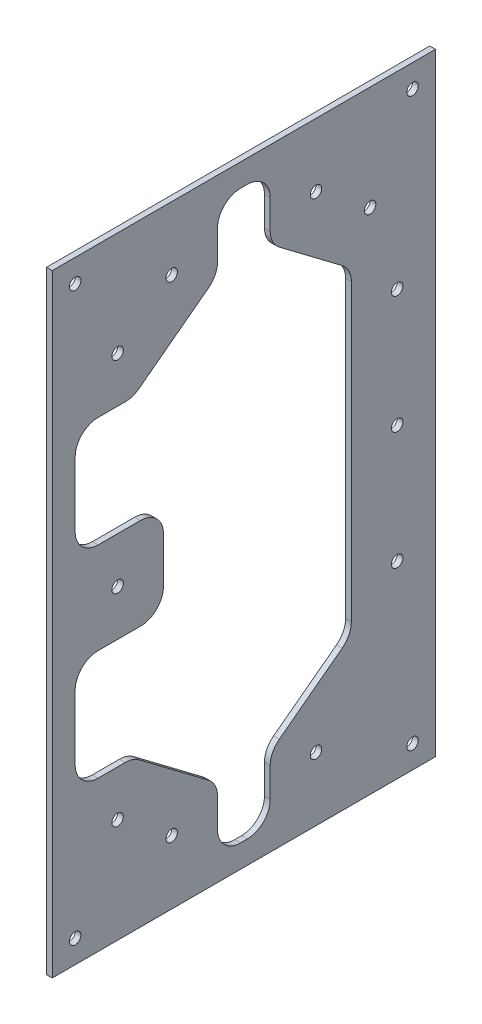
SolidWorks part; units mm, degrees
material "6061-T6 (SS)"
ref_plane "Front Plane" through (0, 0, 0) normal (0, 0, 1) x (1, 0, 0)
ref_plane "Top Plane" through (0, 0, 0) normal (0, 1, 0) x (1, 0, 0)
ref_plane "Right Plane" through (0, 0, 0) normal (1, 0, 0) x (0, 0, -1)
sketch "Sketch1" plane through (0, 0, 0) normal (1, 0, 0) x (0, 0, -1)
  line L0 (0, -169.8625) -> (212.5, -169.8625) construction
  line L1 (0, 0) -> (212.5, 0)
  line L2 (0, 0) -> (0, -339.725)
  line L3 (0, -339.725) -> (212.5, -339.725)
  line L4 (212.5, 0) -> (212.5, -339.725)
  line L5 (153.5, -35.2425) -> (59, -35.2425) construction
  line L6 (191.25, -104.5325) -> (191.25, -169.8625) construction
  line L7 (13.5, -50.2425) -> (59, -50.2425) construction
  line L8 (36.25, -50.2425) -> (36.25, -169.8625) construction
  line L9 (106.25, 0) -> (106.25, -339.725) construction
  line L10 (173.5, -104.5325) -> (191.25, -104.5325) construction
  circle A0 centre (12.7, -12.7) radius 3.175
  circle A1 centre (199.8, -12.7) radius 3.175
  circle A2 centre (66.25, -35.2425) radius 3.175
  circle A3 centre (146.25, -35.2425) radius 3.175
  circle A4 centre (176.25, -57.8625) radius 3.175
  circle A5 centre (36.25, -57.8625) radius 3.175
  circle A6 centre (191.25, -104.5325) radius 3.175
  circle A7 centre (36.25, -169.8625) radius 3.175
  circle A8 centre (191.25, -169.8625) radius 3.175
  circle A9 centre (36.25, -281.8625) radius 3.175
  circle A10 centre (66.25, -304.4825) radius 3.175
  circle A11 centre (12.7, -327.025) radius 3.175
  circle A12 centre (199.8, -327.025) radius 3.175
  circle A13 centre (146.25, -304.4825) radius 3.175
  circle A14 centre (191.25, -235.1925) radius 3.175
  dimension "D1" = 339.725
  dimension "D2" = 212.5
  dimension "D3" = 40
  dimension "D4" = 112
  dimension "D5" = 85
  dimension "D6" = 157.1625
extrude "Boss-Extrude1" add sketch "Sketch1" along normal blind 3.175
sketch "Sketch2" plane through (3.175, 0, 0) normal (1, 0, 0) x (0, 0, -1)
  line L1 (165.85, -88.1617) -> (165.85, -251.5633)
  line L4 (0, 0) -> (0, -339.725)
  line L5 (0, -339.725) -> (212.5, -339.725)
  line L6 (212.5, -339.725) -> (212.5, 0)
  line L7 (212.5, 0) -> (0, 0)
  line L8 (0, 0) -> (0, -339.725)
  line L9 (0, -339.725) -> (212.5, -339.725)
  line L10 (212.5, -339.725) -> (212.5, 0)
  line L11 (212.5, 0) -> (0, 0)
  line L14 (25.4, -144.4625) -> (48.95, -144.4625)
  line L15 (25.4, -83.2625) -> (40.5014, -83.2625)
  line L16 (12.7, -95.9625) -> (12.7, -131.7625)
  line L17 (34.7163, -60.6425) -> (37.7837, -60.6425)
  line L18 (61.65, -70.5625) -> (61.65, -70.522)
  line L19 (61.65, -182.5625) -> (61.65, -157.1625)
  line L20 (36.25, -57.8625) -> (66.25, -35.2425) construction
  line L21 (48.1473, -80.703) -> (86.5959, -51.7127)
  line L22 (91.65, -25.4) -> (91.65, -41.5722)
  line L23 (120.85, -25.4) -> (120.85, -41.5722)
  line L24 (104.35, -12.7) -> (108.15, -12.7)
  line L25 (176.25, -57.8625) -> (146.25, -35.2425) construction
  line L26 (125.9041, -51.7127) -> (160.7959, -78.0212)
  line L27 (0, -169.8625) -> (212.5, -169.8625) construction
  line L28 (176.25, -281.8625) -> (146.25, -304.4825) construction
  line L29 (36.25, -281.8625) -> (66.25, -304.4825) construction
  line L30 (125.9041, -288.0123) -> (160.7959, -261.7038)
  line L31 (104.35, -327.025) -> (108.15, -327.025)
  line L32 (120.85, -314.325) -> (120.85, -298.1528)
  line L33 (91.65, -314.325) -> (91.65, -298.1528)
  line L34 (48.1473, -259.022) -> (86.5959, -288.0123)
  line L35 (61.65, -269.1625) -> (61.65, -269.203)
  line L36 (34.7163, -279.0825) -> (37.7837, -279.0825)
  line L37 (12.7, -243.7625) -> (12.7, -207.9625)
  line L38 (25.4, -256.4625) -> (40.5014, -256.4625)
  line L39 (25.4, -195.2625) -> (48.95, -195.2625)
  circle A0 centre (176.25, -57.8625) radius 3.175 construction
  circle A1 centre (146.25, -35.2425) radius 3.175 construction
  circle A2 centre (66.25, -35.2425) radius 3.175 construction
  circle A3 centre (36.25, -57.8625) radius 3.175 construction
  circle A4 centre (36.25, -169.8625) radius 3.175 construction
  circle A5 centre (36.25, -281.8625) radius 3.175 construction
  circle A6 centre (66.25, -304.4825) radius 3.175 construction
  circle A7 centre (146.25, -304.4825) radius 3.175 construction
  circle A8 centre (191.25, -235.1925) radius 3.175 construction
  circle A9 centre (191.25, -169.8625) radius 3.175 construction
  circle A10 centre (191.25, -104.5325) radius 3.175 construction
  circle A11 centre (176.25, -57.8625) radius 3.175 construction
  circle A12 centre (146.25, -35.2425) radius 3.175 construction
  circle A13 centre (66.25, -35.2425) radius 3.175 construction
  circle A14 centre (36.25, -57.8625) radius 3.175 construction
  circle A15 centre (36.25, -169.8625) radius 3.175 construction
  circle A16 centre (36.25, -281.8625) radius 3.175 construction
  circle A17 centre (66.25, -304.4825) radius 3.175 construction
  circle A18 centre (146.25, -304.4825) radius 3.175 construction
  circle A19 centre (191.25, -235.1925) radius 3.175 construction
  circle A20 centre (191.25, -169.8625) radius 3.175 construction
  circle A21 centre (191.25, -104.5325) radius 3.175 construction
  arc A28 (48.95, -144.4625) -> (61.65, -157.1625) centre (48.95, -157.1625) cw
  arc A29 (12.7, -131.7625) -> (25.4, -144.4625) centre (25.4, -131.7625) ccw
  arc A30 (12.7, -95.9625) -> (25.4, -83.2625) centre (25.4, -95.9625) cw
  arc A33 (165.85, -88.1617) -> (160.7959, -78.0212) centre (153.15, -88.1617) ccw
  arc A34 (125.9041, -51.7127) -> (120.85, -41.5722) centre (133.55, -41.5722) cw
  arc A35 (108.15, -12.7) -> (120.85, -25.4) centre (108.15, -25.4) cw
  arc A36 (104.35, -12.7) -> (91.65, -25.4) centre (104.35, -25.4) ccw
  arc A37 (86.5959, -51.7127) -> (91.65, -41.5722) centre (78.95, -41.5722) ccw
  arc A38 (48.1473, -80.703) -> (40.5014, -83.2625) centre (40.5014, -70.5625) cw
  circle A39 centre (36.25, -281.8625) radius 3.175 construction
  circle A40 centre (66.25, -304.4825) radius 3.175 construction
  circle A41 centre (146.25, -304.4825) radius 3.175 construction
  circle A42 centre (176.25, -281.8625) radius 3.175 construction
  arc A43 (48.1473, -259.022) -> (40.5014, -256.4625) centre (40.5014, -269.1625) ccw
  arc A44 (86.5959, -288.0123) -> (91.65, -298.1528) centre (78.95, -298.1528) cw
  arc A45 (104.35, -327.025) -> (91.65, -314.325) centre (104.35, -314.325) cw
  arc A46 (108.15, -327.025) -> (120.85, -314.325) centre (108.15, -314.325) ccw
  arc A47 (125.9041, -288.0123) -> (120.85, -298.1528) centre (133.55, -298.1528) ccw
  arc A48 (165.85, -251.5633) -> (160.7959, -261.7038) centre (153.15, -251.5633) cw
  arc A49 (12.7, -243.7625) -> (25.4, -256.4625) centre (25.4, -243.7625) ccw
  arc A50 (12.7, -207.9625) -> (25.4, -195.2625) centre (25.4, -207.9625) cw
  arc A51 (48.95, -195.2625) -> (61.65, -182.5625) centre (48.95, -182.5625) ccw
  point P73 (61.65, -83.2625)
  point P78 (61.65, -60.6425)
  point P92 (61.65, -279.0825)
  point P110 (61.65, -169.8625)
  point P114 (165.85, -169.8625)
  point P115 (61.65, -256.4625)
  dimension "D11" = 25.4
  dimension "D13" = 25.4
  dimension "D17" = 12.7
  dimension "D2" = 25.4
  dimension "D7" = 25.4
  dimension "D8" = 25.4
  dimension "D9" = 25.4
  dimension "D14" = 25.4
  dimension "D15" = 12.7
  dimension "D16" = 25.4
  dimension "D1" = 0
extrude "Cut-Extrude1" cut sketch "Sketch2" against normal through all
